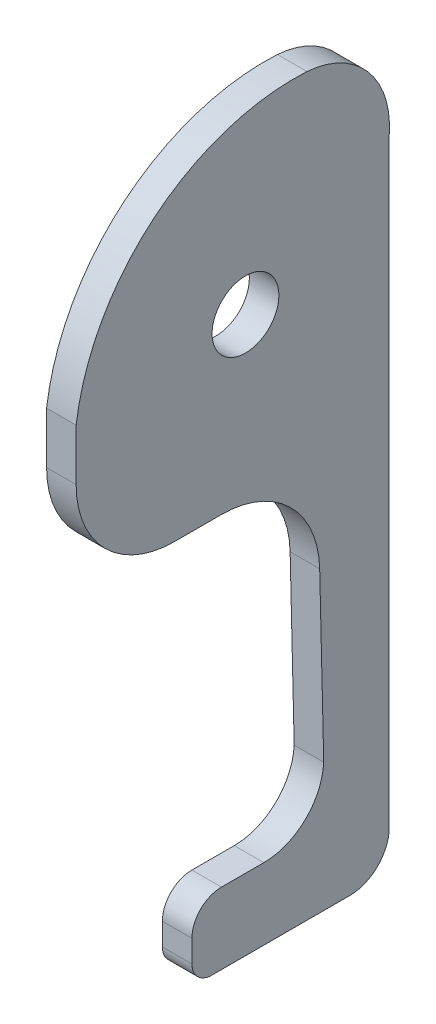
SolidWorks part; units mm, degrees
ref_plane "Front Plane" through (0, 0, 0) normal (0, 0, 1) x (1, 0, 0)
ref_plane "Top Plane" through (0, 0, 0) normal (0, 1, 0) x (1, 0, 0)
ref_plane "Right Plane" through (0, 0, 0) normal (1, 0, 0) x (0, 0, -1)
sketch "Sketch3" plane through (0, 0, 0) normal (1, 0, 0) x (0, 0, -1)
  line L2 (0, -60) -> (0, -86.1848)
  line L3 (50, -136.1848) -> (73.6429, -136.1848)
  line L4 (158.939, -50) -> (158.939, -146.1848)
  line L6 (158.939, -146.1848) -> (158.939, -316.2704)
  line L7 (138.939, -336.2704) -> (117.2626, -336.2704)
  line L9 (117.2626, -336.2704) -> (68.7757, -336.2704)
  line L10 (117.2626, -336.2704) -> (117.2626, -313.0224)
  line L11 (95.2952, -299.9883) -> (73.7757, -299.9883)
  line L12 (58.7757, -326.2704) -> (58.7757, -314.9883)
  line L14 (123.6287, -184.9913) -> (125.6832, -271.0375)
  line L16 (158.939, -11.4803) -> (158.939, -50)
  arc A1 (0, -86.1848) -> (50, -136.1848) centre (50, -86.1848) ccw
  arc A2 (123.6287, -184.9913) -> (73.6429, -136.1848) centre (73.6429, -186.1848) ccw
  arc A4 (95.2952, -299.9883) -> (125.6832, -271.0375) centre (95.2952, -269.5646) ccw
  arc A5 (58.7757, -314.9883) -> (73.7757, -299.9883) centre (73.7757, -314.9883) cw
  arc A6 (58.7757, -326.2704) -> (68.7757, -336.2704) centre (68.7757, -326.2704) ccw
  arc A7 (158.939, -316.2704) -> (138.939, -336.2704) centre (138.939, -316.2704) cw
  arc A8 (0, -60) -> (117.1561, 36.8308) centre (110.8736, -74.8572) cw
  arc A13 (117.1561, 36.8308) -> (158.939, -11.4803) centre (113.892, -8.2162) cw
  point P13 (0, 0)
  dimension "D2" = 50
  dimension "D3" = 50
  dimension "D6" = 15
  dimension "D7" = 10
  dimension "D8" = 20
extrude "Boss-Extrude1" add sketch "Sketch3" along normal blind 15 contours L9 A6 L12 A5 L11 A4 L14 A2 L3 A1 L2 A8 A13 L16 L4 L6 A7 L7
scale "Scale1" scale about centroid uniform scaling yes scale factor 0.147348
sketch "Sketch4" plane through (8.6051, 0, 0) normal (1, 0, 0) x (0, 0, -1)
  line L0 (106.9454, -97.728) -> (106.9454, -142.6381) construction
  circle A0 centre (96.1921, -104.0441) radius 2.5
  dimension "D1" = 5
  dimension "D3" = 10.7533
  dimension "D2" = 13.4347
extrude "Cut-Extrude1" cut sketch "Sketch4" against normal up to next
